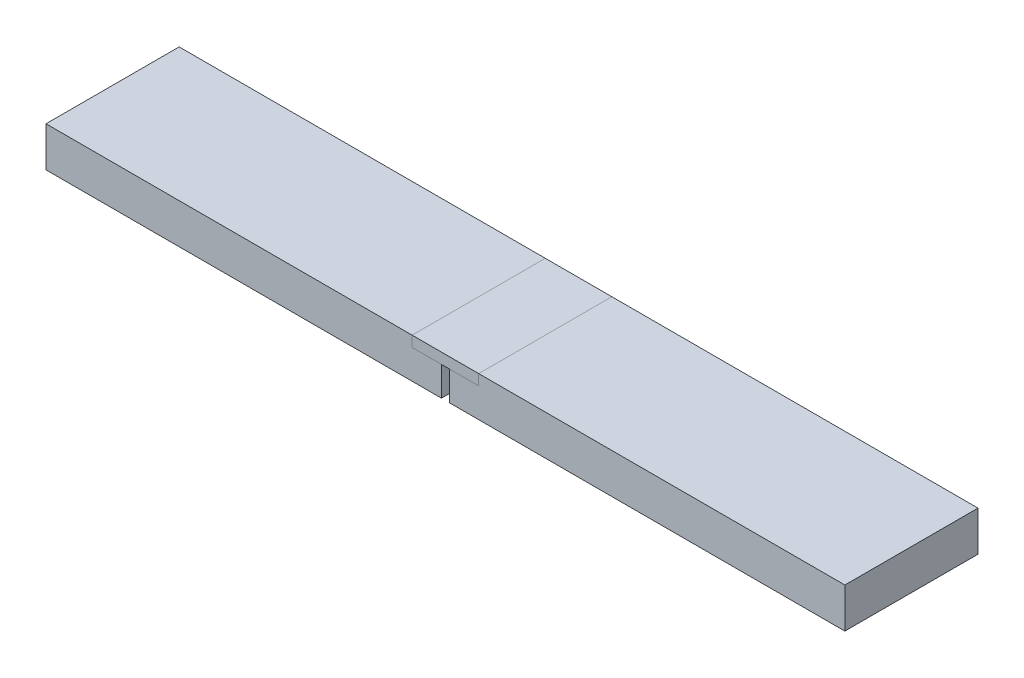
SolidWorks part; units mm, degrees
ref_plane "Front Plane" through (0, 0, 0) normal (0, 0, 1) x (1, 0, 0)
ref_plane "Top Plane" through (0, 0, 0) normal (0, 1, 0) x (1, 0, 0)
ref_plane "Right Plane" through (0, 0, 0) normal (1, 0, 0) x (0, 0, -1)
sketch "Sketch1" plane through (0, 0, 0) normal (0, 1, 0) x (1, 0, 0)
  line L1 (-21.3043, -8.2174) -> (38.6957, -8.2174)
  line L2 (-21.3043, -8.2174) -> (-21.3043, 1.7826)
  line L3 (-21.3043, 1.7826) -> (38.6957, 1.7826)
  line L4 (38.6957, -8.2174) -> (38.6957, 1.7826)
  dimension "D1" = 10
  dimension "D2" = 60
extrude "Boss-Extrude1" add sketch "Sketch1" along normal blind 3 contours L1 L4 L3 L2
sketch "Sketch3" plane through (0, 0, 0) normal (0, -1, 0) x (1, 0, 0)
  line L5 (-21.3043, 8.2174) -> (38.6957, 8.2174) construction
  line L6 (8.3957, 8.2174) -> (8.9957, 8.2174)
  line L7 (8.3957, 8.2174) -> (8.3957, -1.7826)
  line L8 (8.3957, -1.7826) -> (8.9957, -1.7826)
  line L9 (8.9957, 8.2174) -> (8.9957, -1.7826)
  line L10 (-21.3043, -1.7826) -> (38.6957, -1.7826) construction
  line L11 (-21.3043, 8.2174) -> (-21.3043, -1.7826) construction
  dimension "D1" = 0.6
  dimension "D2" = 29.7
extrude "Cut-Extrude1" cut sketch "Sketch3" against normal blind 2.2
sketch "Sketch4" plane through (0, 3, 0) normal (0, 1, 0) x (1, 0, 0)
  line L0 (-21.3043, 1.7826) -> (38.6957, 1.7826) construction
  line L5 (-21.3043, -8.2174) -> (38.6957, -8.2174) construction
  line L20 (6.1957, 1.7826) -> (11.1957, 1.7826)
  line L21 (6.1957, 1.7826) -> (6.1957, -8.2174)
  line L22 (6.1957, -8.2174) -> (11.1957, -8.2174)
  line L23 (11.1957, 1.7826) -> (11.1957, -8.2174)
  line L26 (-21.3043, -8.2174) -> (-21.3043, 1.7826) construction
  dimension "D3" = 27.5
  dimension "D7" = 5
extrude "Cut-Extrude2" cut sketch "Sketch4" against normal blind 0.8
sketch "Sketch5" plane through (0, 2.2, 0) normal (0, 1, 0) x (1, 0, 0)
  line L1 (6.1957, 1.7826) -> (11.1957, 1.7826)
  line L2 (6.1957, 1.7826) -> (6.1957, -8.2174)
  line L3 (6.1957, -8.2174) -> (11.1957, -8.2174)
  line L4 (11.1957, 1.7826) -> (11.1957, -8.2174)
extrude "Boss-Extrude2" add sketch "Sketch5" along normal blind 0.8 separate body
